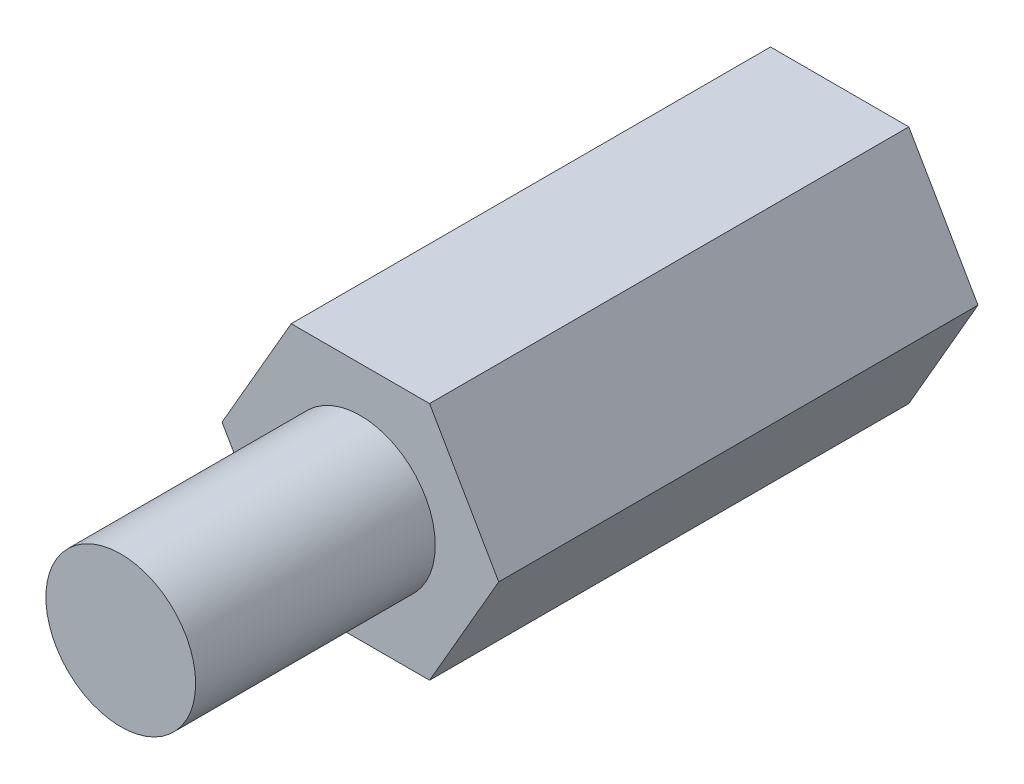
SolidWorks part; units mm, degrees
material "Brass"
ref_plane "Plan de face" through (0, 0, 0) normal (0, 0, 1) x (1, 0, 0)
ref_plane "Plan de dessus" through (0, 0, 0) normal (0, 1, 0) x (1, 0, 0)
ref_plane "Plan de droite" through (0, 0, 0) normal (1, 0, 0) x (0, 0, -1)
sketch "Sketch1" plane through (0, 0, 0) normal (0, 0, 1) x (1, 0, 0)
  line L1 (-1.1547, -2) -> (1.1547, -2)
  line L2 (1.1547, -2) -> (2.3094, 0)
  line L3 (2.3094, 0) -> (1.1547, 2)
  line L4 (1.1547, 2) -> (-1.1547, 2)
  line L5 (-1.1547, 2) -> (-2.3094, 0)
  line L6 (-2.3094, 0) -> (-1.1547, -2)
  circle A0 centre (0, 0) radius 2 construction
  dimension "D1" = 4
extrude "Boss-Extrude1" add sketch "Sketch1" along normal blind 8
sketch "Sketch2" plane through (0, 0, 8) normal (0, 0, 1) x (1, 0, 0)
  circle A0 centre (0, 0) radius 1.25
  dimension "D1" = 2.5
extrude "Boss-Extrude2" add sketch "Sketch2" along normal blind 4
hole_wizard "M2.5 Tapped Hole1" positions "Sketch4" profile "Sketch5" tap size "M2.5" standard "ISO"
sketch "Sketch4" plane through (0, 0, 0) normal (0, 0, -1) x (-1, 0, 0)
  point P0 (0, 0)
sketch "Sketch5" plane through (0, 0, 0) normal (1, 0, 0) x (0, 1, 0)
  line L0 (0, 0) -> (0, 6.1159)
  line L1 (0, 6.1159) -> (1.025, 5.5)
  line L2 (1.025, 5.5) -> (1.025, 0)
  line L5 (1.025, 0) -> (0, 0)
  line L10 (0, 6.1159) -> (-1.025, 5.5) construction
  line L11 (0, -6.35) -> (0, 107.95) construction
  dimension "Tap Drill Dia." = 2.05
  dimension "Tap Drill Depth" = 5.5
  dimension "Drill Angle" = 118
cosmetic thread "Hole Thread1" parameters "D1"=5.5, "D2"=2.5
